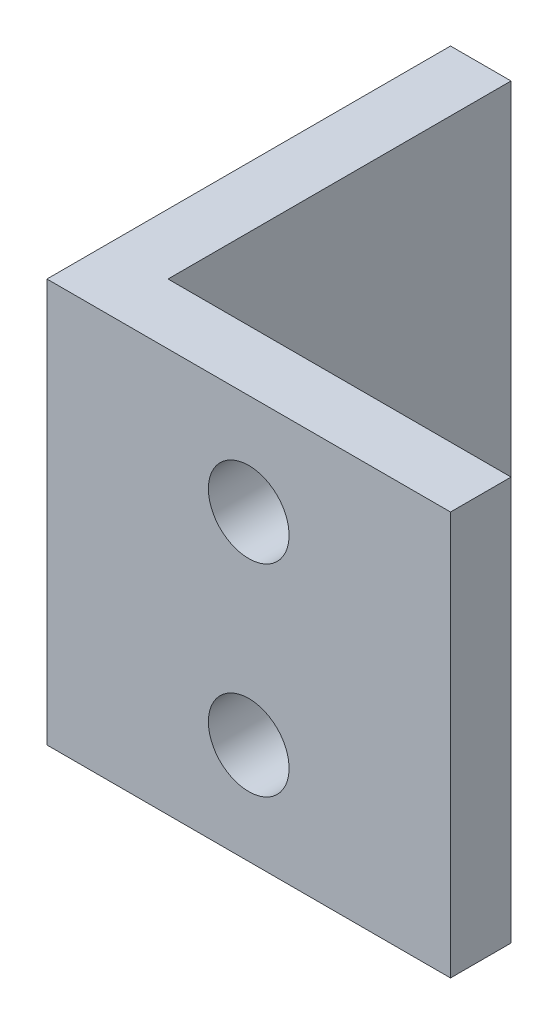
SolidWorks part; units mm, degrees
ref_plane "前视基准面" through (0, 0, 0) normal (0, 0, 1) x (1, 0, 0)
ref_plane "上视基准面" through (0, 0, 0) normal (0, 1, 0) x (1, 0, 0)
ref_plane "右视基准面" through (0, 0, 0) normal (1, 0, 0) x (0, 0, -1)
ref_plane "基准面4" through (0, 160, 0) normal (0, 1, 0) x (1, 0, 0)
sketch "草图1" plane through (0, 160, 0) normal (0, 1, 0) x (1, 0, 0)
  line L0 (59, -20) -> (59, 0)
  line L1 (59, 0) -> (39, 0)
  line L2 (39, 0) -> (39, -20)
  line L3 (39, -20) -> (59, -20)
extrude "凸台-拉伸1" add sketch "草图1" against normal blind 20
sketch "草图2" plane through (0, 140, 0) normal (0, -1, 0) x (1, 0, 0)
  line L0 (59, 0) -> (59, 17)
  line L1 (59, 17) -> (42, 17)
  line L2 (42, 17) -> (42, 0)
  line L3 (42, 0) -> (59, 0)
extrude "切除-拉伸1" cut sketch "草图2" against normal through all
hole_wizard "Ø4.2 (4.2) 直径孔1" positions "草图4" profile "草图3" hole size "Ø4.2" standard "ANSI Metric"
sketch "草图4" plane through (39, 0, 0) normal (-1, 0, 0) x (0, 0, 1)
  point P0 (10, 150)
sketch "草图3" plane through (39, 150, 10) normal (0, 1, 0) x (0, 0, 1)
  line L0 (0, 0) -> (0, 20)
  line L1 (0, 20) -> (2.1, 20)
  line L2 (2.1, 20) -> (2.1, 0)
  line L5 (2.1, 0) -> (0, 0)
  line L11 (0, -6.35) -> (0, 107.95) construction
  dimension "通孔孔直径" = 4.2
  dimension "通孔孔深度" = 20
hole_wizard "Ø4.0 (4) 直径孔1" positions "草图6" profile "草图5" hole size "Ø4.0" standard "ANSI Metric"
sketch "草图6" plane through (0, 0, 17) normal (0, 0, -1) x (-1, 0, 0)
  point P0 (-49, 145)
  point P1 (-49, 155)
sketch "草图5" plane through (49, 145, 17) normal (1, 0, 0) x (0, 1, 0)
  line L0 (0, 0) -> (0, 3)
  line L1 (0, 3) -> (2, 3)
  line L2 (2, 3) -> (2, 0)
  line L5 (2, 0) -> (0, 0)
  line L11 (0, -6.35) -> (0, 107.95) construction
  dimension "通孔孔直径" = 4
  dimension "通孔孔深度" = 3
